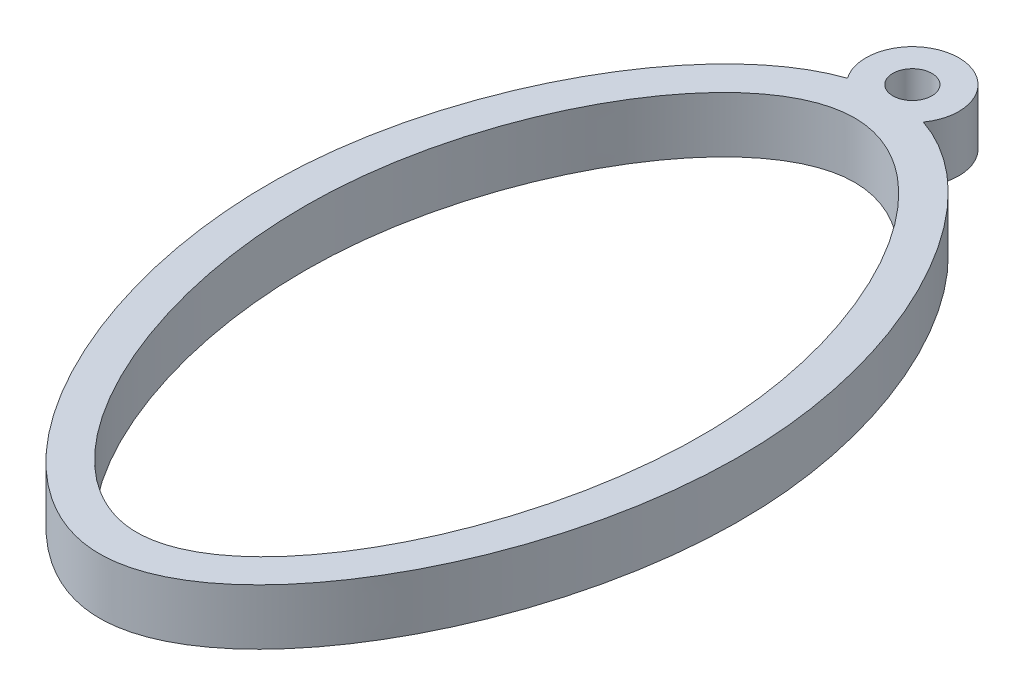
SolidWorks part; units mm, degrees
ref_plane "Front Plane" through (0, 0, 0) normal (0, 0, 1) x (1, 0, 0)
ref_plane "Top Plane" through (0, 0, 0) normal (0, 1, 0) x (1, 0, 0)
ref_plane "Right Plane" through (0, 0, 0) normal (1, 0, 0) x (0, 0, -1)
sketch "Sketch1" plane through (0, 0, 0) normal (0, 1, 0) x (1, 0, 0)
  line L0 (0, 17.3722) -> (0, -21.2327) construction
  line L1 (-10.635, 0) -> (10.635, 0) construction
  line L2 (0, 19.3723) -> (0, -23.2327) construction
  line L3 (-12.635, 0) -> (12.635, 0) construction
  circle A0 centre (0, 20.4722) radius 1.05
  arc A1 (2.0383, 19.0247) -> (-2.0383, 19.0247) centre (0, 20.4722) ccw
  spline S0 degree 3 poles (-16.0361, -1.0206) (0, 25.8645) (16.0361, -1.0206) (0, -32.1127) (-16.0361, -1.0206) (0, 25.8645) (16.0361, -1.0206) knots -0.769144 -0.5 -0.230856 0 0.230856 0.5 0.769144 1 1.230856 1.5 1.769144 only from (0, 17.3722) to (0, 17.3722)
  spline S1 degree 3 poles (-19.0283, -0.9165) (0, 28.8377) (19.0283, -0.9165) (0, -35.1376) (-19.0283, -0.9165) (0, 28.8377) (19.0283, -0.9165) knots -0.766731 -0.5 -0.233269 0 0.233269 0.5 0.766731 1 1.233269 1.5 1.766731 only from (0, 19.3723) to (0, 19.3723)
  dimension "D9" = 2.1
  dimension "D10" = 5
  dimension "D1" = 38.605
  dimension "D2" = 21.27
  dimension "D3" = 17.3722
  dimension "D4" = 10.635
  dimension "D5" = 42.605
  dimension "D6" = 2
  dimension "D7" = 25.27
  dimension "D8" = 2
  dimension "D11" = 3.1
extrude "Boss-Extrude1" add sketch "Sketch1" along normal blind 3 contours A1 S1 A0 | S1 S0
equation "\"D7@Sketch1\"=\"D2@Sketch1\"+4"
equation "\"D5@Sketch1\"=\"D1@Sketch1\"+4"
equation "\"D3@Sketch1\"=\"D1@Sketch1\"*0.45"
equation "\"D4@Sketch1\"=\"D2@Sketch1\"*0.5"
